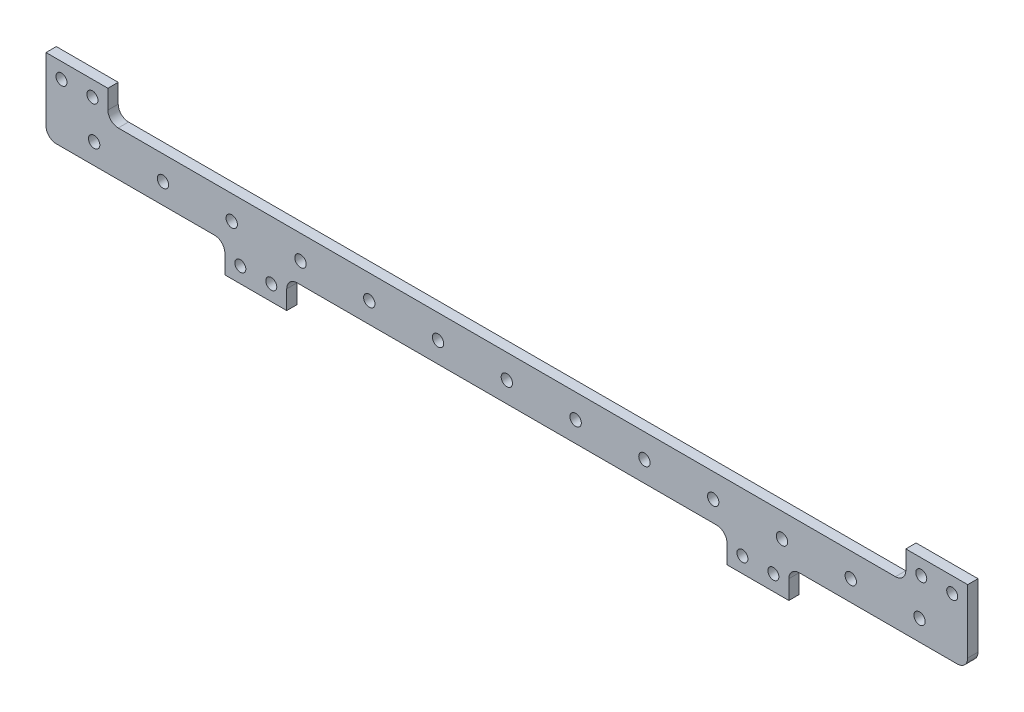
SolidWorks part; units mm, degrees
ref_plane "前视基准面" through (0, 0, 0) normal (0, 0, 1) x (1, 0, 0)
ref_plane "上视基准面" through (0, 0, 0) normal (0, 1, 0) x (1, 0, 0)
ref_plane "右视基准面" through (0, 0, 0) normal (1, 0, 0) x (0, 0, -1)
other "Configuration Table"
sketch "草图1" plane through (0, 0, 0) normal (0, 0, 1) x (1, 0, 0)
  line L0 (-77.5, 4.5) -> (-68.5, 4.5) construction
  line L1 (120.5, 25.5) -> (129.5, 25.5) construction
  line L2 (68.5, 4.5) -> (77.5, 4.5) construction
  line L3 (-129.5, 25.5) -> (-120.5, 25.5) construction
  line L6 (-61, 8.5) -> (61, 8.5)
  line L9 (85, 8.5) -> (131, 8.5)
  line L12 (113, 21.5) -> (-113, 21.5)
  line L15 (-131, 8.5) -> (-85, 8.5)
  line L17 (116, 24.5) -> (116, 30)
  line L18 (116, 30) -> (134, 30)
  line L19 (134, 30) -> (134, 11.5)
  line L20 (-134, 11.5) -> (-134, 30)
  line L21 (-134, 30) -> (-116, 30)
  line L22 (-116, 30) -> (-116, 24.5)
  line L23 (82, 5.5) -> (82, 0)
  line L24 (82, 0) -> (64, 0)
  line L25 (64, 0) -> (64, 5.5)
  line L26 (-82, 5.5) -> (-82, 0)
  line L27 (-82, 0) -> (-64, 0)
  line L28 (-64, 0) -> (-64, 5.5)
  line L29 (-64, 0) -> (64, 0) construction
  circle A0 centre (-77.5, 4.5) radius 1.6
  circle A1 centre (-68.5, 4.5) radius 1.6
  circle A2 centre (120.5, 25.5) radius 1.6
  circle A3 centre (129.5, 25.5) radius 1.6
  circle A4 centre (68.5, 4.5) radius 1.6
  circle A5 centre (77.5, 4.5) radius 1.6
  circle A6 centre (-129.5, 25.5) radius 1.6
  circle A7 centre (-120.5, 25.5) radius 1.6
  arc A8 (-82, 5.5) -> (-85, 8.5) centre (-85, 5.5) ccw
  arc A10 (82, 5.5) -> (85, 8.5) centre (85, 5.5) cw
  arc A15 (131, 8.5) -> (134, 11.5) centre (131, 11.5) ccw
  arc A19 (-134, 11.5) -> (-131, 8.5) centre (-131, 11.5) ccw
  arc A20 (-61, 8.5) -> (-64, 5.5) centre (-61, 5.5) ccw
  arc A21 (61, 8.5) -> (64, 5.5) centre (61, 5.5) cw
  arc A22 (113, 21.5) -> (116, 24.5) centre (113, 24.5) ccw
  arc A23 (-113, 21.5) -> (-116, 24.5) centre (-113, 24.5) cw
  point P17 (0, 8.5)
  point P30 (0, 21.5)
  point P36 (0, 0)
  point P42 (-82, 8.5)
  point P45 (-64, 5.5)
  point P49 (82, 8.5)
  point P52 (64, 5.5)
  point P61 (134, 8.5)
  point P72 (-134, 8.5)
  dimension "D1" = 3.2
  dimension "D3" = 3.2
  dimension "D5" = 3.2
  dimension "D7" = 3.2
  dimension "D18" = 4.5
  dimension "D24" = 3
  dimension "D25" = 3
  dimension "D11" = 8.5
  dimension "D2" = 9
  dimension "D4" = 9
  dimension "D6" = 9
  dimension "D8" = 9
  dimension "D9" = 18
  dimension "D10" = 128
  dimension "D12" = 30
  dimension "D13" = 268
  dimension "D16" = 4.5
  dimension "D17" = 4.5
  dimension "D19" = 4.5
  dimension "D20" = 4.5
  dimension "D21" = 4.5
  dimension "D22" = 4.5
  dimension "D23" = 4.5
extrude "凸台-拉伸1" add sketch "草图1" along normal blind 3
sketch "草图2" plane through (0, 0, 0) normal (0, 0, -1) x (-1, 0, 0)
  line L0 (-134, 14.5) -> (134, 14.5)
  line L1 (-134, 11.5) -> (-134, 30) construction
  line L2 (134, 30) -> (134, 11.5) construction
  line L3 (-113, 21.5) -> (113, 21.5) construction
  point P8 (-114, 14.5)
  dimension "D1" = 7
  dimension "D2" = 20
sketch "草图5" plane through (0, 0, 0) normal (0, 0, -1) x (-1, 0, 0)
  point P0 (0, 14.5)
hole_wizard "孔2" positions "草图5" profile "草图6" legacy end condition up to next
sketch "草图6" plane through (0, 14.5, 0) normal (1, 0, 0) x (0, 1, 0)
  line L0 (0, 0) -> (0, 3)
  line L1 (0, 3) -> (1.65, 3)
  line L2 (1.65, 3) -> (1.65, 0)
  line L3 (1.65, 0) -> (0, 0)
  line L4 (0, 110) -> (0, -10) construction
  dimension "直径" = 3.3
  dimension "深度" = 3
pattern_linear "阵列(线性)1" count 7 spacing 20 along (1, 0, 0) count 7 spacing 20 along (-1, 0, 0) of "孔2"
